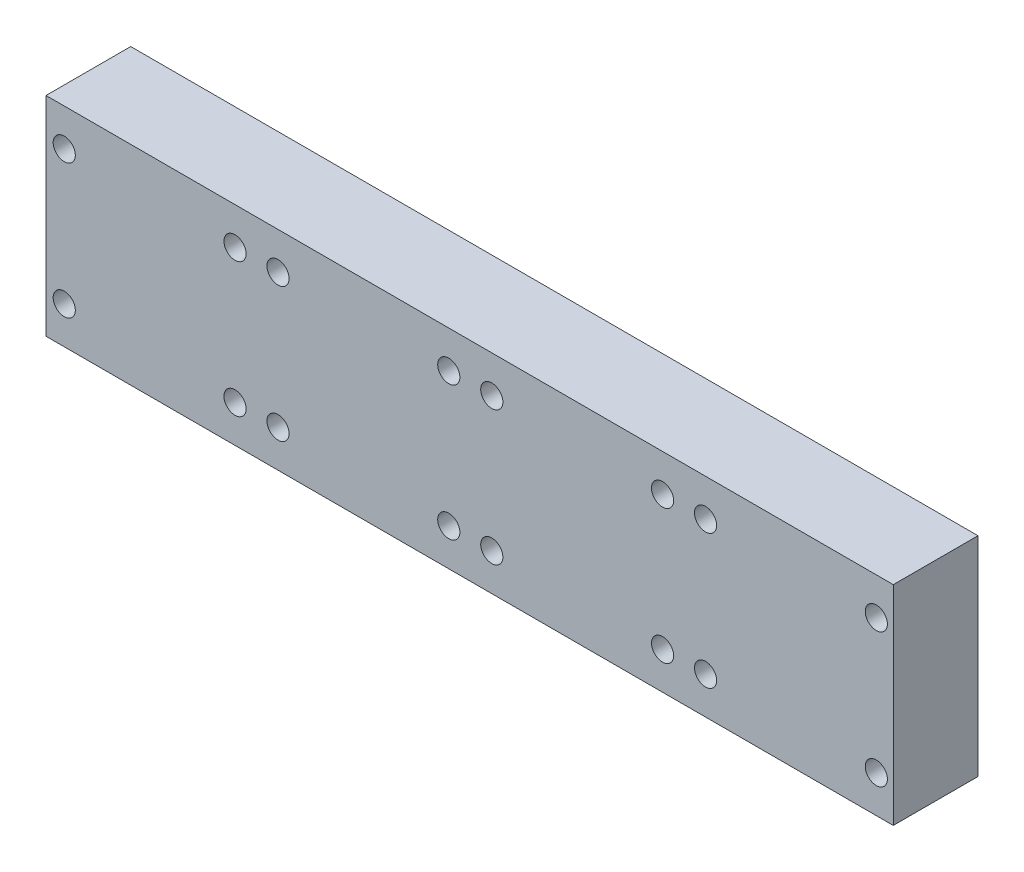
SolidWorks part; units mm, degrees
ref_plane "Plan de face" through (0, 0, 0) normal (0, 0, 1) x (1, 0, 0)
ref_plane "Plan de dessus" through (0, 0, 0) normal (0, 1, 0) x (1, 0, 0)
ref_plane "Plan de droite" through (0, 0, 0) normal (1, 0, 0) x (0, 0, -1)
sketch "Esquisse1" plane through (0, 0, 0) normal (0, 0, 1) x (1, 0, 0)
  line L1 (0, 0) -> (130, 0)
  line L2 (0, 0) -> (0, 32)
  line L3 (0, 32) -> (130, 32)
  line L4 (130, 0) -> (130, 32)
  line L5 (2.8, 26.3) -> (29, 26.3) construction
  line L6 (2.8, 26.3) -> (2.8, 5.7) construction
  line L7 (2.8, 5.7) -> (29, 5.7) construction
  line L8 (29, 26.3) -> (29, 5.7) construction
  circle A0 centre (2.8, 26.3) radius 1.5
  circle A1 centre (29, 26.3) radius 1.5
  circle A2 centre (2.8, 5.7) radius 1.5
  circle A3 centre (29, 5.7) radius 1.5
  dimension "D7" = 3
  dimension "D8" = 3
  dimension "D9" = 3
  dimension "D10" = 3
  dimension "D1" = 130
  dimension "D2" = 32
  dimension "D3" = 26.2
  dimension "D4" = 5.7
  dimension "D5" = 5.7
  dimension "D6" = 2.8
extrude "Boss.-Extru.1" add sketch "Esquisse1" along normal blind 13
hole_wizard "Dégagement M31" positions "Esquisse2" profile "Esquisse3" hole size "M3" standard "ISO" end condition up to next
sketch "Esquisse2" plane through (0, 0, 13) normal (0, 0, 1) x (1, 0, 0)
  point P0 (2.8, 26.3)
  point P3 (29, 26.3)
  point P6 (2.8, 5.7)
  point P9 (29, 5.7)
sketch "Esquisse3" plane through (2.8, 26.3, 13) normal (1, 0, 0) x (0, -1, 0)
  line L0 (0, 0) -> (0, 13)
  line L1 (0, 13) -> (1.7, 13)
  line L2 (1.7, 13) -> (1.7, 0)
  line L5 (1.7, 0) -> (0, 0)
  line L11 (0, -6.35) -> (0, 107.95) construction
  dimension "Diamètre du perçage jusqu'au prochain" = 3.4
  dimension "Profondeur du perçage jusqu'au prochain" = 13
pattern_linear "Répétition linéaire1" count 4 spacing 32.8 along (1, 0, 0) of "Dégagement M31"
